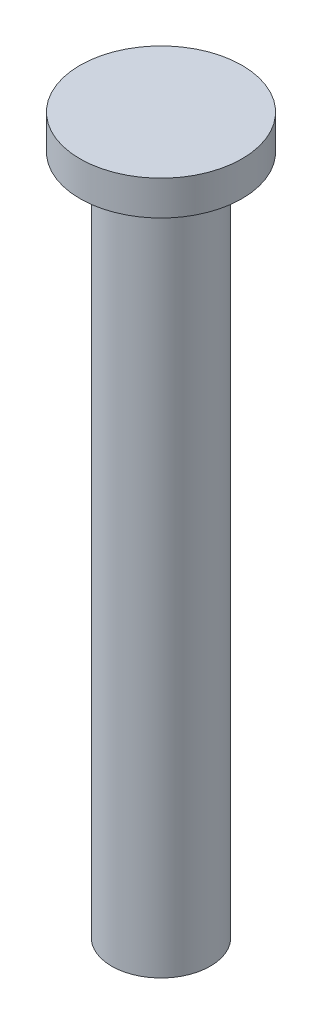
SolidWorks part; units mm, degrees
ref_plane "Front" through (0, 0, 0) normal (0, 0, 1) x (1, 0, 0)
ref_plane "Top" through (0, 0, 0) normal (0, 1, 0) x (1, 0, 0)
ref_plane "Right" through (0, 0, 0) normal (1, 0, 0) x (0, 0, -1)
sketch "Sketch1" plane through (0, 0, 0) normal (0, 1, 0) x (1, 0, 0)
  circle A0 centre (0, 0) radius 10
extrude "Boss-Extrude1" add sketch "Sketch1" against normal blind 138
sketch "Sketch2" plane through (0, 0, 0) normal (0, 1, 0) x (1, 0, 0)
  circle A0 centre (0, 0) radius 16.4314
extrude "Boss-Extrude2" add sketch "Sketch2" along normal blind 7
